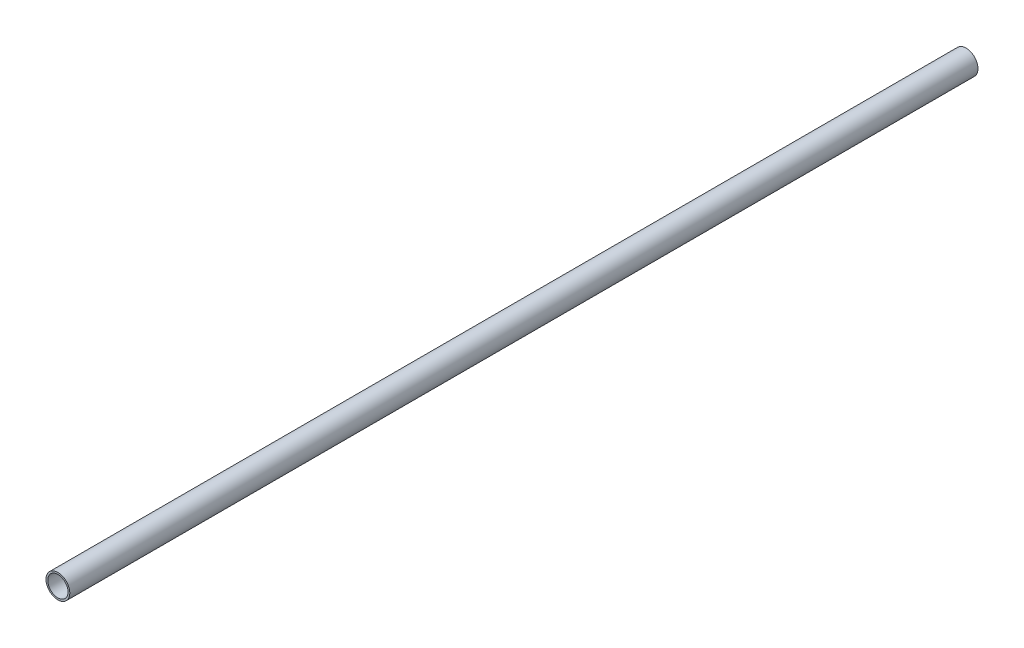
SolidWorks part; units mm, degrees
material "Thornel Mat VMA"
ref_plane "Front Plane" through (0, 0, 0) normal (0, 0, 1) x (1, 0, 0)
ref_plane "Top Plane" through (0, 0, 0) normal (0, 1, 0) x (1, 0, 0)
ref_plane "Right Plane" through (0, 0, 0) normal (1, 0, 0) x (0, 0, -1)
sketch "Sketch1" plane through (0, 0, 0) normal (1, 0, 0) x (0, 0, -1)
  line L0 (-76.537, 0) -> (66.8488, 0) construction
  line L1 (-228.6, 5.1054) -> (228.6, 5.1054)
  line L2 (228.6, 5.1054) -> (228.6, 5.9944)
  line L3 (228.6, 5.9944) -> (-228.6, 5.9944)
  line L4 (-228.6, 5.9944) -> (-228.6, 5.1054)
  dimension "D1" = 5.9944
  dimension "D2" = 0.889
  dimension "D3" = 457.2
  dimension "D4" = 228.6
revolve "Revolve1" add sketch "Sketch1" angle 360 about L0
scale "Scale1" scale about centroid uniform scaling yes scale factor 0.6
